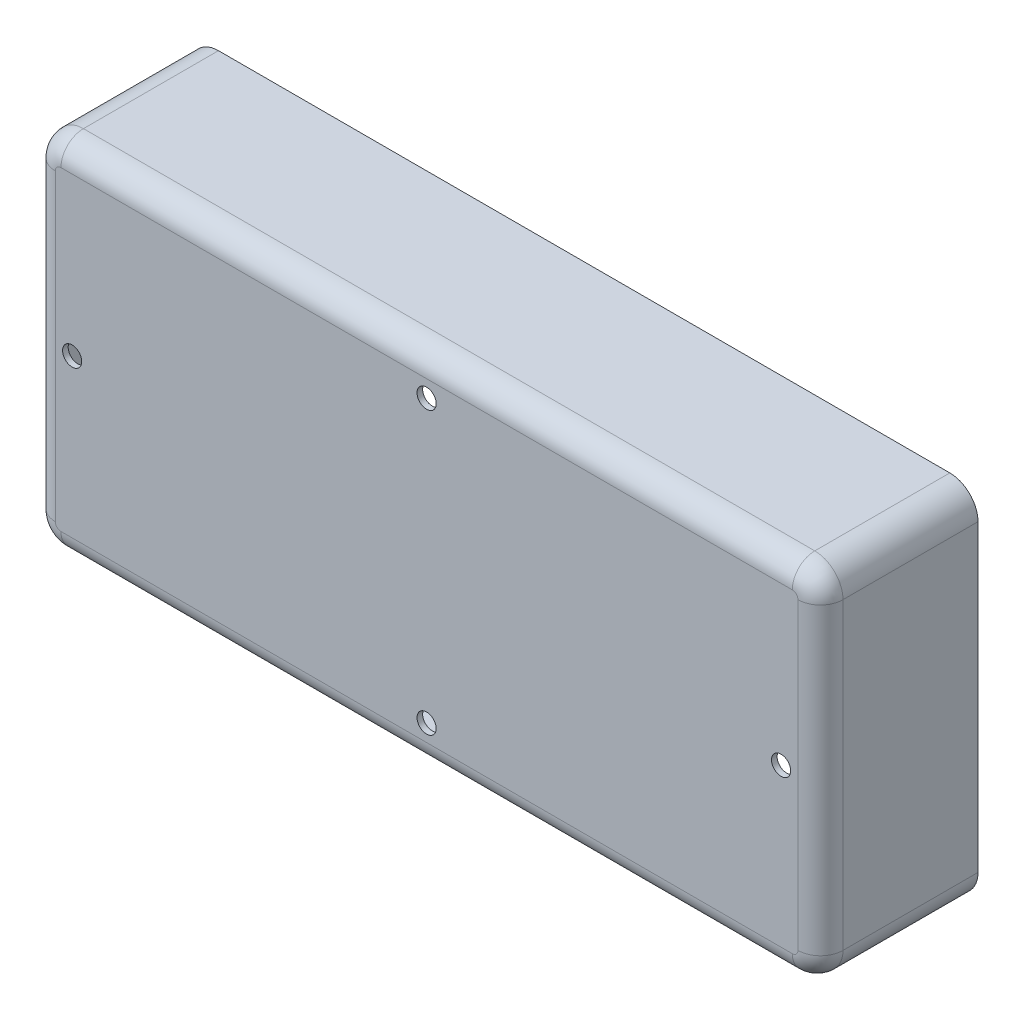
SolidWorks part; units mm, degrees
material "ASTM A36 Steel"
ref_plane "Front Plane" through (0, 0, 0) normal (0, 0, 1) x (1, 0, 0)
ref_plane "Top Plane" through (0, 0, 0) normal (0, 1, 0) x (1, 0, 0)
ref_plane "Right Plane" through (0, 0, 0) normal (1, 0, 0) x (0, 0, -1)
sketch "Sketch1" plane through (0, 0, 0) normal (0, 0, 1) x (1, 0, 0)
  line L1 (-103.1748, 50.8) -> (103.1748, 50.8)
  line L2 (-111.125, 42.8498) -> (-111.125, -42.8498)
  line L3 (-103.1748, -50.8) -> (103.1748, -50.8)
  line L4 (111.125, 42.8498) -> (111.125, -42.8498)
  arc A0 (-111.125, -42.8498) -> (-103.1748, -50.8) centre (-103.1748, -42.8498) ccw
  arc A1 (-103.1748, 50.8) -> (-111.125, 42.8498) centre (-103.1748, 42.8498) ccw
  arc A2 (103.1748, 50.8) -> (111.125, 42.8498) centre (103.1748, 42.8498) cw
  arc A3 (103.1748, -50.8) -> (111.125, -42.8498) centre (103.1748, -42.8498) ccw
  point P12 (111.125, 0)
  point P13 (0, 50.8)
  dimension "D1" = 7.9502
  dimension "D2" = 101.6
  dimension "D3" = 222.25
extrude "Boss-Extrude1" add sketch "Sketch1" along normal blind 44.45
fillet "Fillet1" radius 6.35 8 edges at (-111.125, 0, 44.45) (-108.7964, 48.4714, 44.45) (0, 50.8, 44.45) (108.7964, 48.4714, 44.45) (111.125, 0, 44.45) (108.7964, -48.4714, 44.45) (0, -50.8, 44.45) (-108.7964, -48.4714, 44.45)
shell "Shell1" thickness 1.5875
sketch "Sketch2" plane through (0, 0, 44.45) normal (0, 0, 1) x (1, 0, 0)
  circle A0 centre (0, 39.6875) radius 2.7051
  circle A1 centre (0, -39.6875) radius 2.7051
  circle A2 centre (100.0125, 0) radius 2.7051
  circle A3 centre (-100.0125, 0) radius 2.7051
  dimension "D1" = 5.4102
extrude "Cut-Extrude1" cut sketch "Sketch2" against normal up to next
sketch "Sketch3" plane through (0, 0, 44.45) normal (0, 0, 1) x (1, 0, 0)
  circle A0 centre (0, 39.6875) radius 3.9751
  circle A1 centre (0, 39.6875) radius 1.905
  circle A2 centre (-100.0125, 0) radius 3.9751
  circle A3 centre (-100.0125, 0) radius 1.905
  circle A4 centre (0, -39.6875) radius 3.9751
  circle A5 centre (0, -39.6875) radius 1.905
  circle A6 centre (100.0125, 0) radius 3.9751
  circle A7 centre (100.0125, 0) radius 1.905
  dimension "D1" = 7.9502
  dimension "D2" = 3.81
extrude "Boss-Extrude2" [suppressed] add sketch "Sketch3" along normal blind 2.3622
